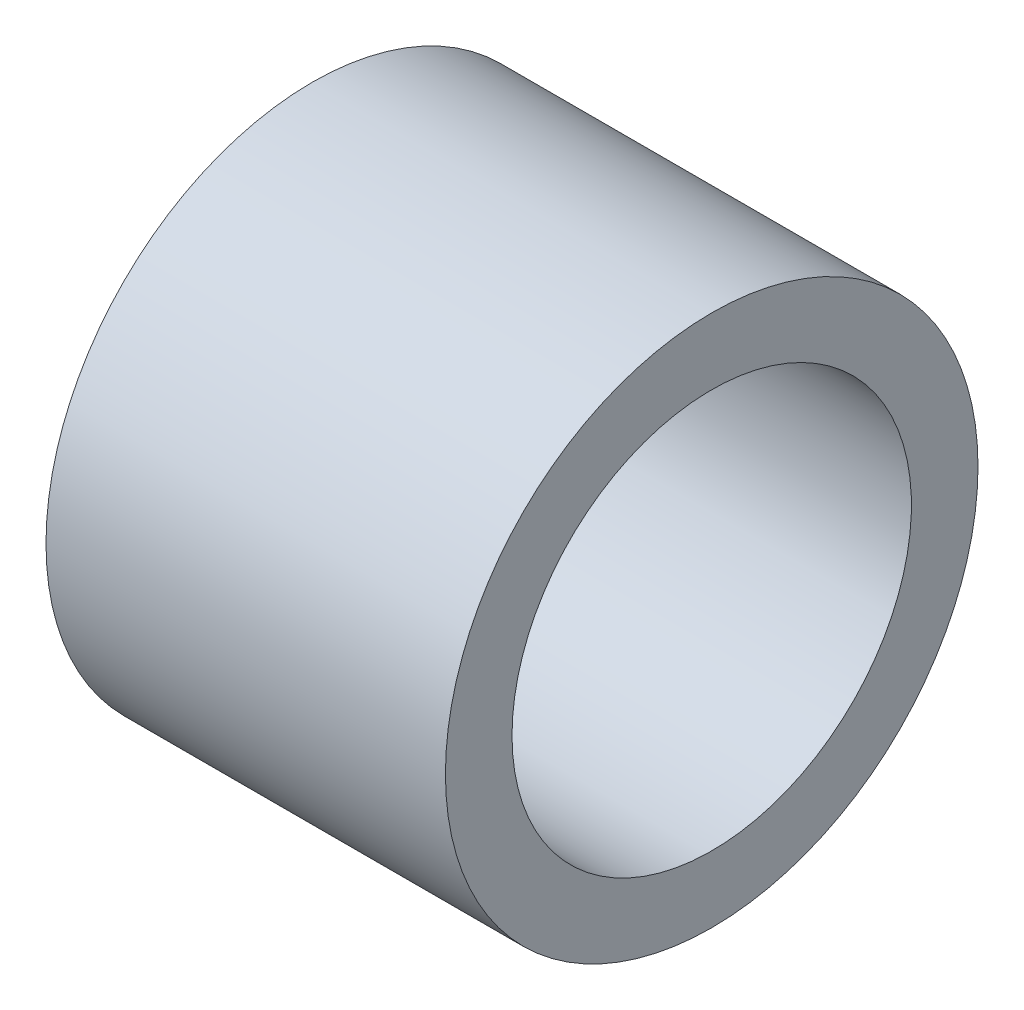
SolidWorks part; units mm, degrees
ref_plane "Front Plane" through (0, 0, 0) normal (1, 0, 0) x (0, 1, 0)
ref_plane "Top Plane" through (0, 0, 0) normal (0, 0, 1) x (0, 1, 0)
ref_plane "Right Plane" through (0, 0, 0) normal (0, 1, 0) x (-1, 0, 0)
sketch "Sketch1" plane through (0, 0, 0) normal (1, 0, 0) x (0, 1, 0)
  circle A0 centre (0, 0) radius 12.7
  circle A1 centre (0, 0) radius 9.525
  dimension "D1" = 25.4
  dimension "D2" = 19.05
extrude "Boss-Extrude1" add sketch "Sketch1" along normal blind 19.05
